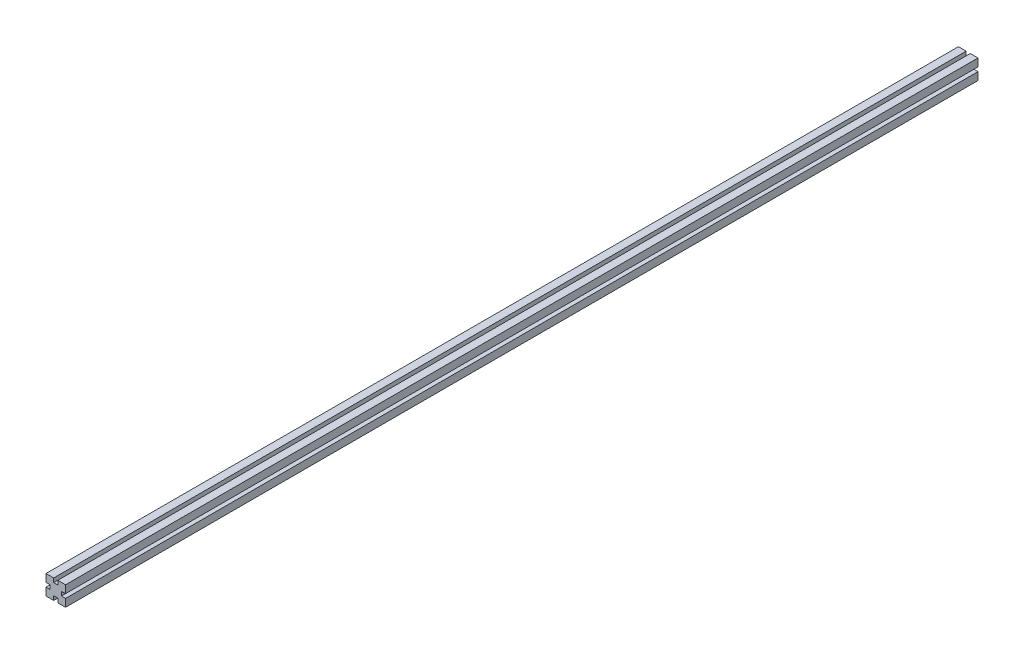
SolidWorks part; units mm, degrees
ref_plane "Front Plane" through (0, 0, 0) normal (0, 0, 1) x (1, 0, 0)
ref_plane "Top Plane" through (0, 0, 0) normal (0, 1, 0) x (1, 0, 0)
ref_plane "Right Plane" through (0, 0, 0) normal (1, 0, 0) x (0, 0, -1)
sketch "Sketch1" plane through (0, 0, 0) normal (0, 0, 1) x (1, 0, 0)
  line L0 (-19.05, -19.05) -> (-4, -19.05)
  line L1 (-4, -19.05) -> (-4, -11.05)
  line L2 (-4, -11.05) -> (4, -11.05)
  line L3 (4, -11.05) -> (4, -19.05)
  line L4 (4, -19.05) -> (19.05, -19.05)
  line L5 (19.05, -19.05) -> (19.05, -4)
  line L6 (19.05, -4) -> (11.05, -4)
  line L7 (11.05, -4) -> (11.05, 4)
  line L8 (11.05, 4) -> (19.05, 4)
  line L9 (19.05, 4) -> (19.05, 19.05)
  line L10 (19.05, 19.05) -> (4, 19.05)
  line L11 (4, 19.05) -> (4, 11.05)
  line L12 (4, 11.05) -> (-4, 11.05)
  line L13 (-4, 11.05) -> (-4, 19.05)
  line L14 (-4, 19.05) -> (-19.05, 19.05)
  line L15 (-19.05, 19.05) -> (-19.05, 4)
  line L16 (-19.05, 4) -> (-11.05, 4)
  line L17 (-11.05, 4) -> (-11.05, -4)
  line L18 (-11.05, -4) -> (-19.05, -4)
  line L19 (-19.05, -4) -> (-19.05, -19.05)
extrude "Profile" add sketch "Sketch1" along normal blind 1778
equation "\"length\" = 1778.0mm"
equation "\"D1@Profile\" = \"length\""
